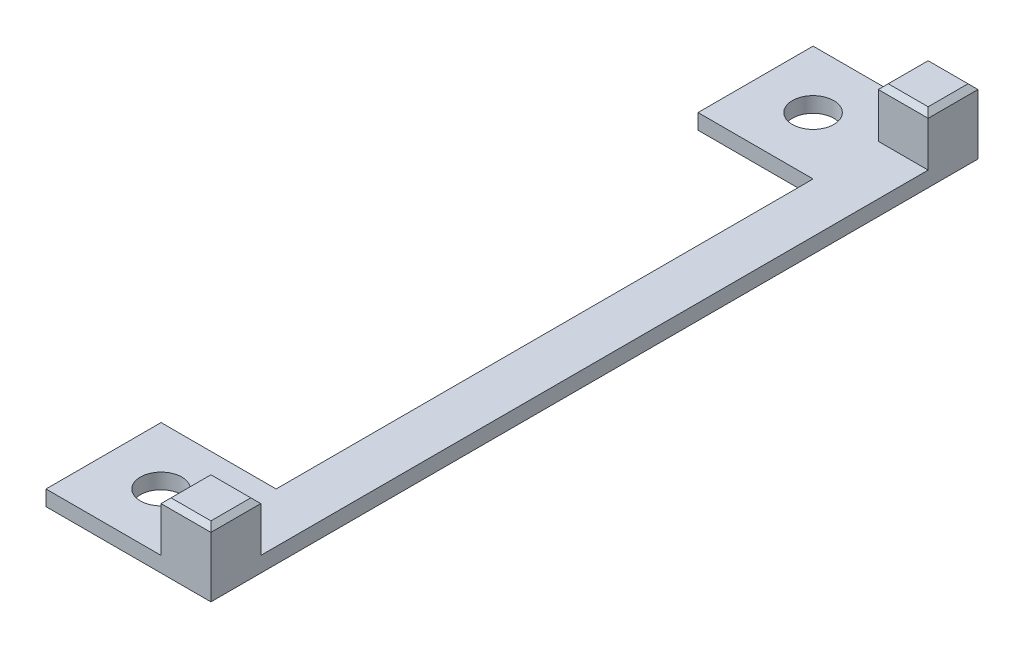
SolidWorks part; units mm, degrees
ref_plane "Front Plane" through (0, 0, 0) normal (0, 0, 1) x (1, 0, 0)
ref_plane "Top Plane" through (0, 0, 0) normal (0, 1, 0) x (1, 0, 0)
ref_plane "Right Plane" through (0, 0, 0) normal (1, 0, 0) x (0, 0, -1)
sketch "Sketch2" plane through (0, 0, 0) normal (0, 1, 0) x (1, 0, 0)
  line L1 (-3.4064, 3.2674) -> (3.0936, 3.2674)
  line L2 (-3.4064, 3.2674) -> (-3.4064, -3.2326)
  line L3 (-3.4064, -3.2326) -> (3.0936, -3.2326)
  line L4 (3.0936, 3.2674) -> (3.0936, -3.2326)
  dimension "D1" = 6.5
  dimension "D2" = 6.5
extrude "Boss-Extrude1" add sketch "Sketch2" along normal blind 8.5
sketch "Sketch4" plane through (-3.4064, 0, 0) normal (-1, 0, 0) x (0, 0, 1)
  line L1 (-3.2674, 0) -> (11.7326, 0)
  line L2 (-3.2674, 0) -> (-3.2674, 2)
  line L3 (-3.2674, 2) -> (11.7326, 2)
  line L4 (11.7326, 0) -> (11.7326, 2)
  dimension "D1" = 2
  dimension "D2" = 15
extrude "Boss-Extrude2" add sketch "Sketch4" along normal blind 15
sketch "Sketch5" plane through (0, 2, 0) normal (0, 1, 0) x (1, 0, 0)
  line L0 (-18.4064, -11.7326) -> (-18.4064, 3.2674) construction
  line L1 (-18.4064, 3.2674) -> (-3.4064, 3.2674) construction
  circle A0 centre (-10.9064, -4.2326) radius 2.7
  dimension "D1" = 5.4
  dimension "D2" = 7.5
  dimension "D3" = 7.5
extrude "Cut-Extrude1" cut sketch "Sketch5" against normal through all
mirror "Mirror3" about plane through (-18.4064, 0, 11.7326) normal (0, 0, -1) of bodies 103
move or copy body "Body-Move/Copy3" bodies to move or copy 107 copy no translate (0, 0, 70) parameters "D1"=0, "D2"=0, "D3"=70
sketch "Sketch6" plane through (0, 0, 0) normal (0, 1, 0) x (1, 0, 0)
  line L1 (-3.4064, -90.2326) -> (3.0936, -90.2326)
  line L2 (-3.4064, -90.2326) -> (-3.4064, -3.2326)
  line L3 (-3.4064, -3.2326) -> (3.0936, -3.2326)
  line L4 (3.0936, -90.2326) -> (3.0936, -3.2326)
extrude "Boss-Extrude3" add sketch "Sketch6" along normal blind 2
sketch "Sketch7" plane through (-3.4064, 0, 0) normal (-1, 0, 0) x (0, 0, 1)
  line L0 (2.5826, 8.5) -> (3.2326, 7.85)
  line L1 (-3.2674, 8.5) -> (3.2326, 8.5) construction
  line L2 (3.2326, 8.5) -> (3.2326, 2) construction
  line L4 (2.5826, 8.5) -> (3.2326, 8.5)
  line L5 (3.2326, 8.5) -> (3.2326, 7.85)
  dimension "D1" = 0.65
  dimension "D2" = 0.65
sketch "Sketch10" plane through (0, 0, -3.2674) normal (0, 0, -1) x (-1, 0, 0)
  line L0 (-2.4436, 8.5) -> (-3.0936, 7.85)
  line L1 (-3.0936, 8.5) -> (3.4064, 8.5) construction
  line L2 (-3.0936, 8.5) -> (-3.0936, 0) construction
  line L3 (-3.0936, 7.85) -> (-3.0936, 8.5)
  line L4 (-3.0936, 8.5) -> (-2.4436, 8.5)
  dimension "D1" = 0.65
  dimension "D2" = 0.65
extrude "Cut-Extrude3" cut sketch "Sketch10" against normal through all
extrude "Cut-Extrude4" cut sketch "Sketch7" against normal through all
sketch "Sketch11" plane through (0, 0, -3.2674) normal (0, 0, -1) x (-1, 0, 0)
  line L0 (2.7564, 8.5) -> (3.4064, 7.85)
  line L1 (-2.4436, 8.5) -> (3.4064, 8.5) construction
  line L2 (3.4064, 8.5) -> (3.4064, 2) construction
  line L3 (3.4064, 7.85) -> (3.4064, 8.5)
  line L4 (3.4064, 8.5) -> (2.7564, 8.5)
  dimension "D1" = 0.65
  dimension "D2" = 0.65
sketch "Sketch12" plane through (-3.4064, 0, 0) normal (-1, 0, 0) x (0, 0, 1)
  line L0 (-2.6174, 8.5) -> (-3.2674, 7.85)
  line L1 (-3.2674, 8.5) -> (2.5826, 8.5) construction
  line L2 (-3.2674, 8.5) -> (-3.2674, 2) construction
  line L3 (-3.2674, 7.85) -> (-3.2674, 8.5)
  line L4 (-3.2674, 7.85) -> (-3.2674, 8.5) construction
  line L5 (-3.2674, 8.5) -> (-2.6174, 8.5)
  dimension "D1" = 0.65
  dimension "D2" = 0.65
extrude "Cut-Extrude5" cut sketch "Sketch12" against normal through all
sketch "Sketch13" plane through (-3.4064, 0, 0) normal (-1, 0, 0) x (0, 0, 1)
  line L0 (90.8826, 8.5) -> (90.2326, 7.85)
  line L1 (96.7326, 8.5) -> (90.2326, 8.5) construction
  line L2 (90.2326, 8.5) -> (90.2326, 2) construction
  line L3 (90.2326, 7.85) -> (90.2326, 8.5)
  line L4 (90.2326, 8.5) -> (90.8826, 8.5)
  line L5 (96.0826, 8.5) -> (96.7326, 7.85)
  line L6 (96.7326, 8.5) -> (96.7326, 2) construction
  line L7 (96.7326, 7.85) -> (96.7326, 8.5)
  line L8 (96.7326, 8.5) -> (96.0826, 8.5)
  dimension "D1" = 0.65
  dimension "D2" = 0.65
  dimension "D3" = 0.65
  dimension "D4" = 0.65
extrude "Cut-Extrude6" cut sketch "Sketch13" against normal through all
extrude "Cut-Extrude7" cut sketch "Sketch11" against normal through all
